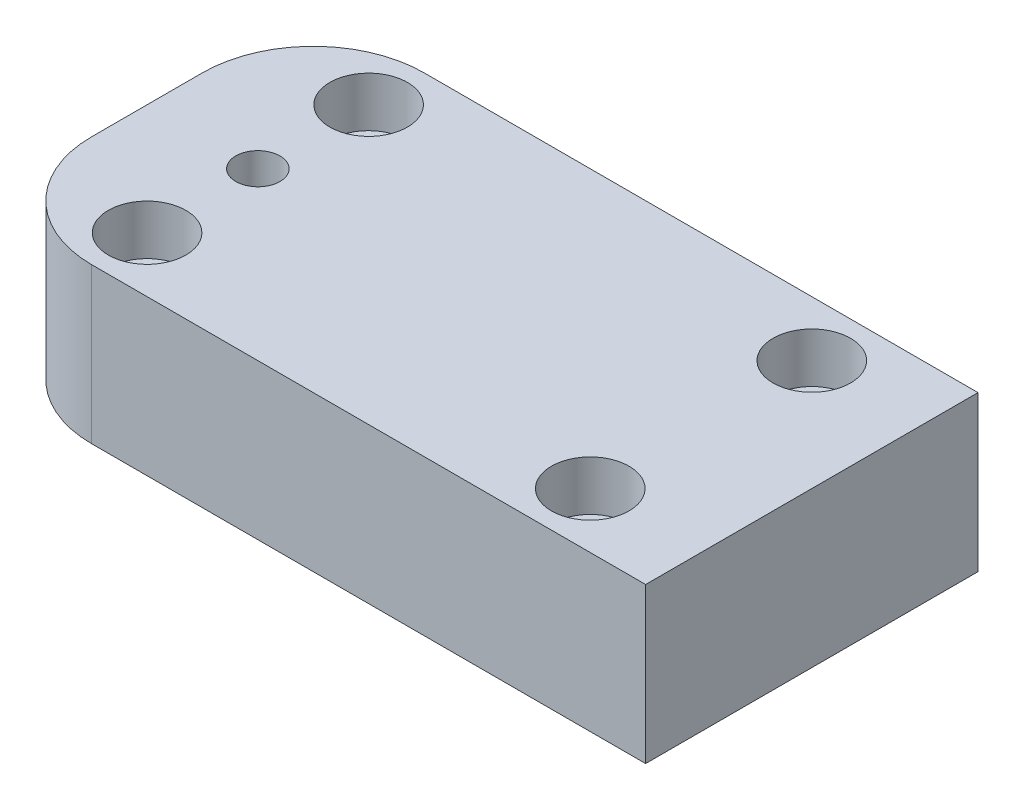
SolidWorks part; units mm, degrees
ref_plane "前视基准面" through (0, 0, 0) normal (0, 0, 1) x (1, 0, 0)
ref_plane "上视基准面" through (0, 0, 0) normal (0, 1, 0) x (1, 0, 0)
ref_plane "右视基准面" through (0, 0, 0) normal (1, 0, 0) x (0, 0, -1)
sketch "草图1" plane through (0, 0, 0) normal (0, 1, 0) x (1, 0, 0)
  line L0 (-30, 0) -> (30, 0) construction
  line L1 (-30, -15) -> (30, -15)
  line L2 (-30, -15) -> (-30, 15)
  line L3 (-30, 15) -> (30, 15)
  line L4 (30, -15) -> (30, 15)
  line L5 (-30, -15) -> (30, 15) construction
  line L6 (-30, 15) -> (30, -15) construction
  line L8 (20, -10) -> (-20, -10) construction
  line L9 (20, -10) -> (20, 10) construction
  line L10 (20, 10) -> (-20, 10) construction
  line L11 (-20, -10) -> (-20, 10) construction
  line L12 (20, -10) -> (-20, 10) construction
  line L13 (20, 10) -> (-20, -10) construction
  circle A0 centre (-20, 0) radius 2
  circle A1 centre (-20, 10) radius 1.75
  circle A2 centre (20, 10) radius 1.75
  circle A3 centre (-20, -10) radius 1.75
  circle A4 centre (20, -10) radius 1.75
  point P0 (0, 0)
  point P10 (0, 0)
  dimension "D3" = 4
  dimension "D4" = 10
  dimension "D7" = 3.5
  dimension "D1" = 30
  dimension "D2" = 60
  dimension "D5" = 40
  dimension "D6" = 20
extrude "凸台-拉伸1" add sketch "草图1" along normal blind 14
fillet "圆角1" radius 10 2 edges at (-30, 7, 15) (-30, 7, -15)
sketch "草图2" plane through (0, 14, 0) normal (0, 1, 0) x (1, 0, 0)
  circle A2 centre (-20, 10) radius 3.5
  circle A3 centre (-20, 10) radius 3.5
  circle A5 centre (-20, -10) radius 3.5
  circle A6 centre (-20, -10) radius 3.5
  circle A8 centre (20, 10) radius 3.5
  circle A9 centre (20, 10) radius 3.5
  circle A11 centre (20, -10) radius 3.5
  circle A12 centre (20, -10) radius 3.5
  dimension "D1" = 1.75
  dimension "D2" = 1.75
  dimension "D3" = 1.75
  dimension "D4" = 1.75
extrude "切除-拉伸1" cut sketch "草图2" against normal blind 4.5
